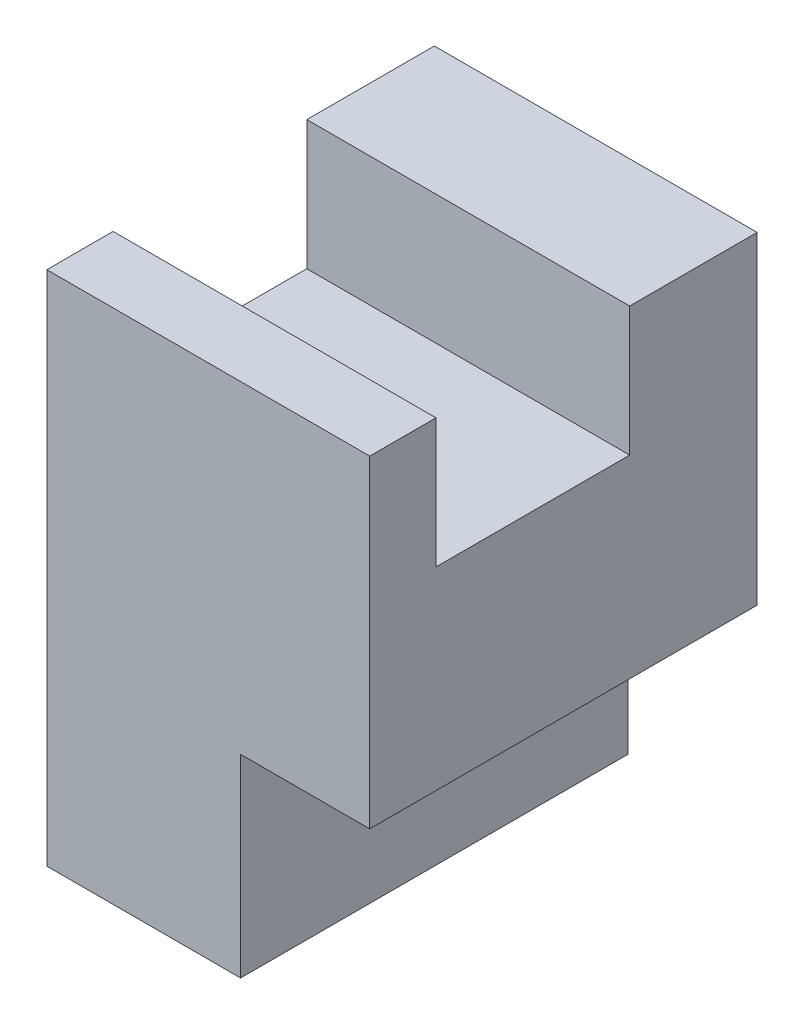
SolidWorks part; units mm, degrees
ref_plane "Ön Düzlem" through (0, 0, 0) normal (0, 0, 1) x (1, 0, 0)
ref_plane "Üst Düzlem" through (0, 0, 0) normal (0, 1, 0) x (1, 0, 0)
ref_plane "Sağ Düzlem" through (0, 0, 0) normal (1, 0, 0) x (0, 0, -1)
sketch "Sketch1" plane through (0, 0, 0) normal (0, 0, 1) x (1, 0, 0)
  line L0 (0, 0) -> (15000, 0)
  line L1 (0, 0) -> (0, 40000)
  line L2 (15000, 0) -> (15000, 15000)
  line L3 (15000, 15000) -> (25000, 15000)
  line L4 (25000, 15000) -> (25000, 40000)
  line L5 (25000, 40000) -> (0, 40000)
extrude "Boss-Extrude1" add sketch "Sketch1" along normal blind 30000
sketch "Sketch2" plane through (0, 40000, 0) normal (0, 1, 0) x (1, 0, 0)
  line L0 (0, -30000) -> (0, -24869.9615)
  line L1 (0, -30000) -> (0, 0) construction
  line L2 (0, -24869.9615) -> (25000, -24869.9615)
  line L3 (25000, -30000) -> (25000, 0) construction
  line L4 (25000, -24869.9615) -> (25000, -9869.9615)
  line L5 (25000, -9869.9615) -> (0, -9869.9615)
  line L6 (0, -9869.9615) -> (0, -24869.9615)
extrude "Cut-Extrude1" cut sketch "Sketch2" against normal blind 10000 contours L2 L4 L5 L6
